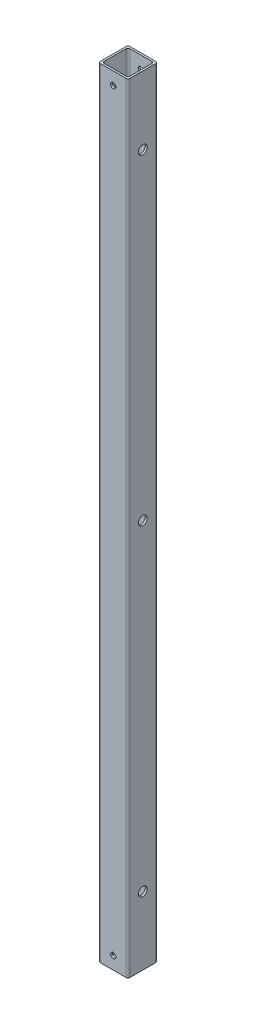
SolidWorks part; units mm, degrees
ref_plane "Front Plane" through (0, 0, 0) normal (0, 0, 1) x (1, 0, 0)
ref_plane "Top Plane" through (0, 0, 0) normal (0, 1, 0) x (1, 0, 0)
ref_plane "Right Plane" through (0, 0, 0) normal (1, 0, 0) x (0, 0, -1)
sketch "Sketch1" plane through (0, 0, 0) normal (0, 1, 0) x (1, 0, 0)
  line L0 (8.382, -8.382) -> (8.382, 8.382)
  line L1 (-9.652, -9.652) -> (9.652, -9.652)
  line L2 (-9.652, -9.652) -> (-9.652, 9.652)
  line L3 (-9.652, 9.652) -> (9.652, 9.652)
  line L4 (9.652, -9.652) -> (9.652, 9.652)
  line L5 (-9.652, -9.652) -> (9.652, 9.652) construction
  line L6 (-9.652, 9.652) -> (9.652, -9.652) construction
  line L7 (-8.382, 8.382) -> (8.382, 8.382)
  line L8 (-8.382, -8.382) -> (-8.382, 8.382)
  line L9 (-8.382, -8.382) -> (8.382, -8.382)
  point P0 (0, 0)
  dimension "D1" = 19.304
  dimension "D2" = 1.27
extrude "Boss-Extrude1" add sketch "Sketch1" along normal blind 508
fillet "Fillet1" radius 1.27 8 edges at (-9.652, 254, 9.652) (-9.652, 254, -9.652) (9.652, 254, -9.652) (9.652, 254, 9.652) (-8.382, 254, -8.382) (8.382, 254, 8.382) (8.382, 254, -8.382) (-8.382, 254, 8.382)
hole_wizard "#1 (0.228) Diameter Hole2" positions "Sketch4" profile "Sketch5" hole size "#1" standard "ANSI Inch" end condition through all
sketch "Sketch4" plane through (-9.652, 0, 0) normal (-1, 0, 0) x (0, 0, 1)
  line L0 (0, 0) -> (0, 508) construction
  line L1 (-8.382, 0) -> (8.382, 0) construction
  line L2 (-8.382, 508) -> (8.382, 508) construction
  point P8 (0, 44.45)
  point P34 (0, 254)
  point P35 (0, 463.55)
  dimension "D1" = 44.45
  dimension "D2" = 3
sketch "Sketch5" plane through (-9.652, 463.55, 0) normal (0, 1, 0) x (0, 0, 1)
  line L0 (0, 0) -> (0, 19.304)
  line L1 (0, 19.304) -> (2.8956, 19.304)
  line L2 (2.8956, 19.304) -> (2.8956, 0)
  line L5 (2.8956, 0) -> (0, 0)
  line L11 (0, -6.35) -> (0, 107.95) construction
  dimension "Thru Hole Dia." = 5.7912
  dimension "Thru Hole Depth" = 19.304
hole_wizard "#8-32 Tapped Hole1" positions "Sketch6" profile "Sketch8" tap size "#8-32" standard "ANSI Inch" end condition through all
sketch "Sketch6" plane through (0, 0, 9.652) normal (0, 0, 1) x (1, 0, 0)
  line L0 (-8.382, 508) -> (8.382, 508) construction
  line L1 (-8.382, 0) -> (8.382, 0) construction
  line L2 (-8.382, 508) -> (-8.382, 0) construction
  point P0 (0, 499.745)
  point P5 (0, 8.255)
  dimension "D1" = 8.255
  dimension "D2" = 8.255
  dimension "D3" = 8.382
sketch "Sketch8" plane through (0, 499.745, 9.652) normal (1, 0, 0) x (0, -1, 0)
  line L0 (0, 0) -> (0, 19.304)
  line L1 (0, 19.304) -> (1.7272, 19.304)
  line L2 (1.7272, 19.304) -> (1.7272, 0)
  line L5 (1.7272, 0) -> (0, 0)
  line L11 (0, -6.35) -> (0, 107.95) construction
  dimension "Thru Tap Drill Dia." = 3.4544
  dimension "Thru Tap Drill Depth" = 19.304
cosmetic thread "Hole Thread1" parameters "D2"=4.1656
cosmetic thread "Hole Thread2" parameters "D2"=4.1656
ref_plane "Plane1" through (-8.382, 508, 9.652) normal (1, 0, 0) x (0, 0, -1)
